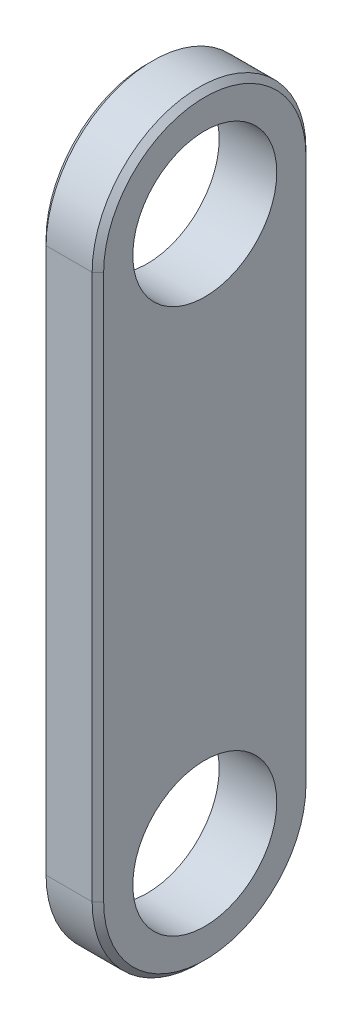
SolidWorks part; units mm, degrees
ref_plane "Front Plane" through (0, 0, 0) normal (1, 0, 0) x (0, 1, 0)
ref_plane "Top Plane" through (0, 0, 0) normal (0, 0, 1) x (0, 1, 0)
ref_plane "Right Plane" through (0, 0, 0) normal (0, 1, 0) x (-1, 0, 0)
sketch "Sketch1" plane through (0, 0, 0) normal (1, 0, 0) x (0, 1, 0)
  line L0 (94.6779, 0) -> (-94.6779, 0) construction
  line L1 (94.6779, -37.1286) -> (-94.6779, -37.1286)
  line L2 (94.6779, 37.1286) -> (-94.6779, 37.1286)
  arc A0 (94.6779, -37.1286) -> (94.6779, 37.1286) centre (94.6779, 0) ccw
  arc A1 (-94.6779, 37.1286) -> (-94.6779, -37.1286) centre (-94.6779, 0) ccw
  circle A2 centre (-94.6779, 0) radius 25
  circle A3 centre (94.6779, 0) radius 25
  point P2 (0, 0)
  dimension "D1" = 50
extrude "Boss-Extrude1" add sketch "Sketch1" along normal mid plane 20
chamfer "Chamfer1" distance 2 angle 45 8 edges at (-10, 0, -37.1286) (-10, 131.8064, 0) (-10, -131.8064, 0) (-10, 0, 37.1286) (10, 0, -37.1286) (10, 131.8064, 0) (10, -131.8064, 0) (10, 0, 37.1286)
